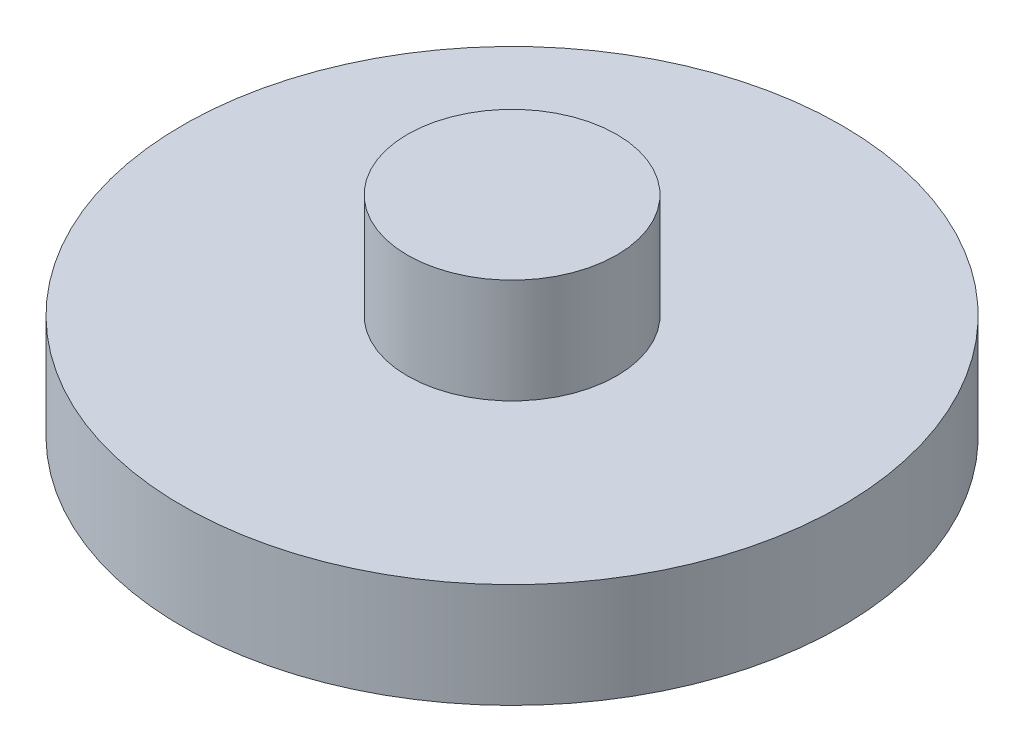
SolidWorks part; units mm, degrees
ref_plane "Front" through (0, 0, 0) normal (0, 0, 1) x (1, 0, 0)
ref_plane "Top" through (0, 0, 0) normal (0, 1, 0) x (1, 0, 0)
ref_plane "Side" through (0, 0, 0) normal (1, 0, 0) x (0, 0, -1)
sketch "Sketch1" plane through (0, 0, 0) normal (0, 0, 1) x (1, 0, 0)
  line L0 (0, 0) -> (0, 44.1652) construction
  line L1 (0, 0) -> (-15.75, 0)
  line L2 (-15.75, 0) -> (-15.75, 5)
  line L3 (-15.75, 5) -> (-5, 5)
  line L4 (-5, 5) -> (-5, 10)
  line L5 (-5, 10) -> (0, 10)
  line L6 (0, 10) -> (0, 0)
  dimension "D1" = 31.5
  dimension "D2" = 10
  dimension "D3" = 5
  dimension "D4" = 5
revolve "Revolve1" add sketch "Sketch1" angle 360 about L0
